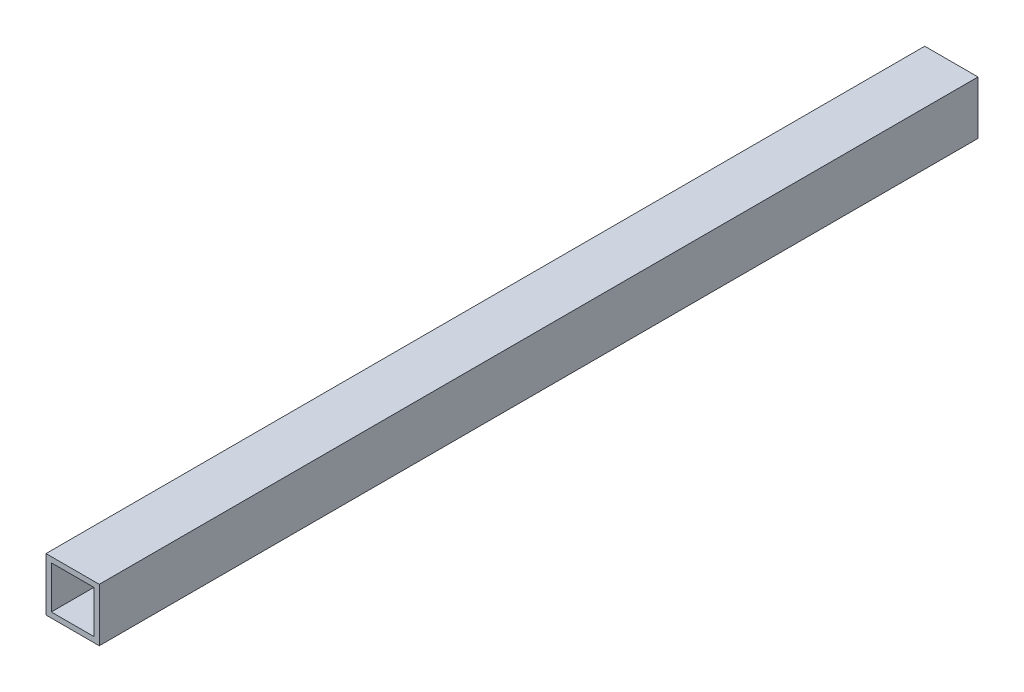
SolidWorks part; units mm, degrees
material "6063-O, Extruded Rod (SS)"
ref_plane "Front Plane" through (0, 0, 0) normal (0, 0, 1) x (1, 0, 0)
ref_plane "Top Plane" through (0, 0, 0) normal (0, 1, 0) x (1, 0, 0)
ref_plane "Right Plane" through (0, 0, 0) normal (1, 0, 0) x (0, 0, -1)
sketch "Sketch1" plane through (0, 0, 0) normal (0, 0, 1) x (1, 0, 0)
  line L0 (-10.16, 10.16) -> (10.16, 10.16)
  line L1 (-12.7, -12.7) -> (12.7, -12.7)
  line L2 (-12.7, -12.7) -> (-12.7, 12.7)
  line L3 (-12.7, 12.7) -> (12.7, 12.7)
  line L4 (12.7, -12.7) -> (12.7, 12.7)
  line L5 (-12.7, -12.7) -> (12.7, 12.7) construction
  line L6 (-12.7, 12.7) -> (12.7, -12.7) construction
  line L7 (10.16, -10.16) -> (10.16, 10.16)
  line L8 (-10.16, -10.16) -> (10.16, -10.16)
  line L9 (-10.16, -10.16) -> (-10.16, 10.16)
  point P0 (0, 0)
  dimension "D1" = 25.4
  dimension "D2" = 25.4
  dimension "D3" = 2.54
extrude "Boss-Extrude1" add sketch "Sketch1" along normal mid plane 419.1
